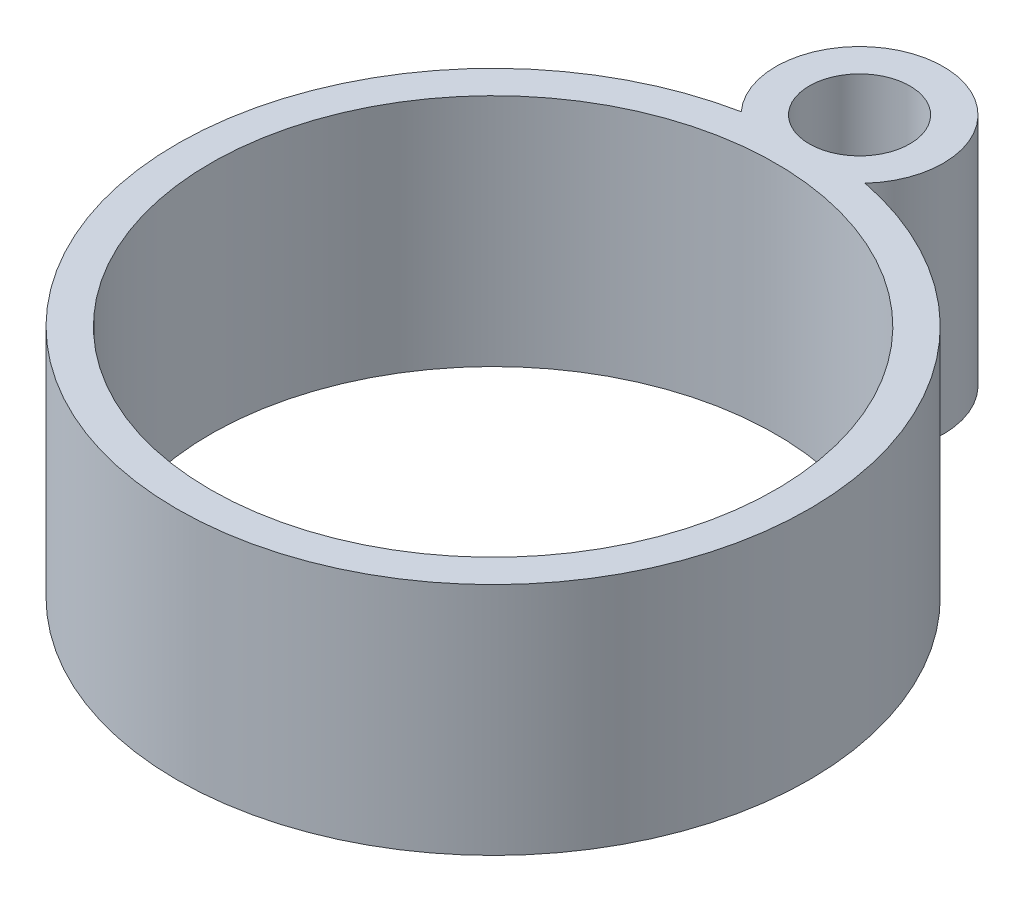
SolidWorks part; units mm, degrees
ref_plane "Front Plane" through (0, 0, 0) normal (0, 0, 1) x (1, 0, 0)
ref_plane "Top Plane" through (0, 0, 0) normal (0, 1, 0) x (1, 0, 0)
ref_plane "Right Plane" through (0, 0, 0) normal (1, 0, 0) x (0, 0, -1)
sketch "Sketch2" plane through (0, 0, 0) normal (0, 1, 0) x (1, 0, 0)
  circle A0 centre (0, 0) radius 8.435
  circle A1 centre (0, 0) radius 9.435
  circle A2 centre (0, 10.935) radius 2.5
  circle A3 centre (0, 10.935) radius 1.5
  dimension "D1" = 16.87
  dimension "D2" = 18.87
  dimension "D3" = 5
  dimension "D4" = 3
extrude "Boss-Extrude1" add sketch "Sketch2" along normal blind 7 contours A2 A0 A1 | A1 A2 A3 | A2 A1
